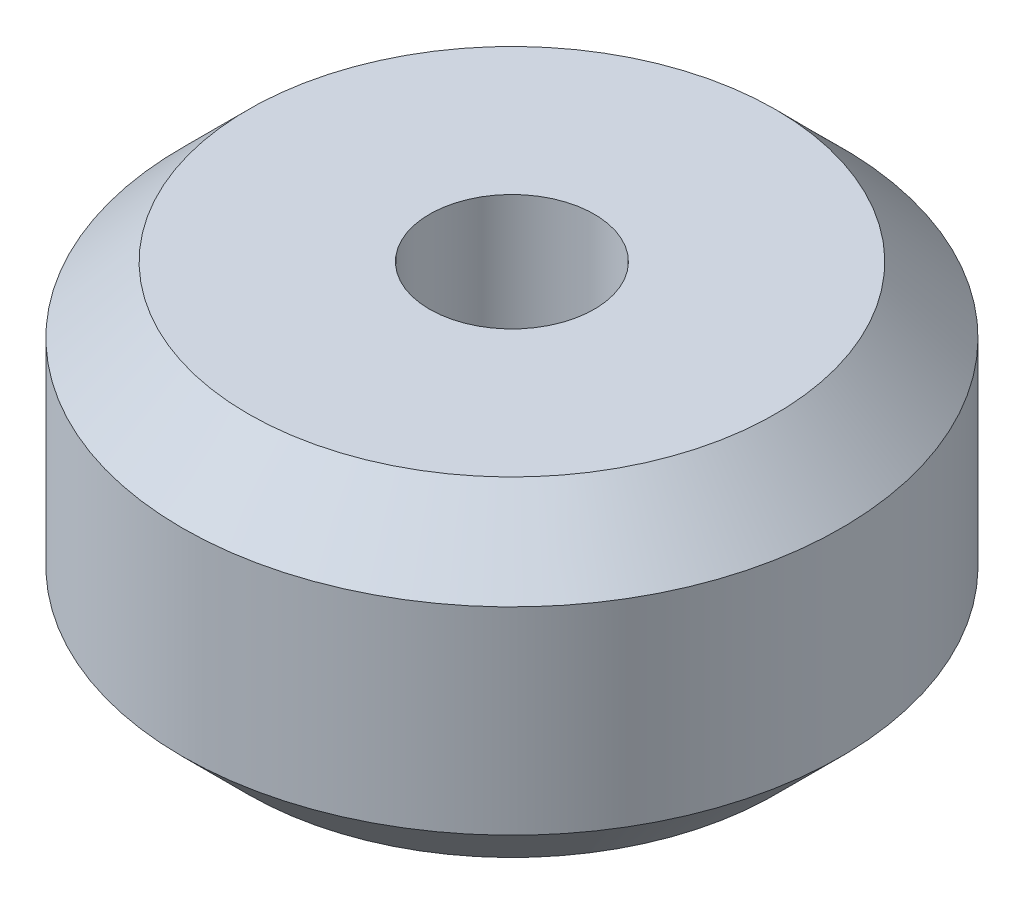
SolidWorks part; units mm, degrees
ref_plane "Front Plane" through (0, 0, 0) normal (0, 0, 1) x (1, 0, 0)
ref_plane "Top Plane" through (0, 0, 0) normal (0, 1, 0) x (1, 0, 0)
ref_plane "Right Plane" through (0, 0, 0) normal (1, 0, 0) x (0, 0, -1)
sketch "Sketch1" plane through (0, 0, 0) normal (0, 0, 1) x (1, 0, 0)
  line L0 (0, 23.8923) -> (0, -23.4261) construction
  line L1 (28.4376, 0) -> (-34.1873, 0) construction
  line L12 (-10, -3) -> (-10, -5.2)
  line L13 (-8, -5) -> (-2.5, -5)
  line L14 (-2.5, -5) -> (-2.5, 5)
  line L15 (-2.5, 5) -> (-8, 5)
  line L16 (-10, 3) -> (-8, 5)
  line L17 (-10, -3) -> (-8, -5)
  line L18 (-10, 3) -> (-10, -3)
  dimension "D1" = 6
  dimension "D2" = 10
  dimension "D3" = 2.5
  dimension "D4" = 7.5
  dimension "D5" = 45
  dimension "D6" = 45
  dimension "D7" = 2
revolve "Revolve1" add sketch "Sketch1" angle 360 about L0
